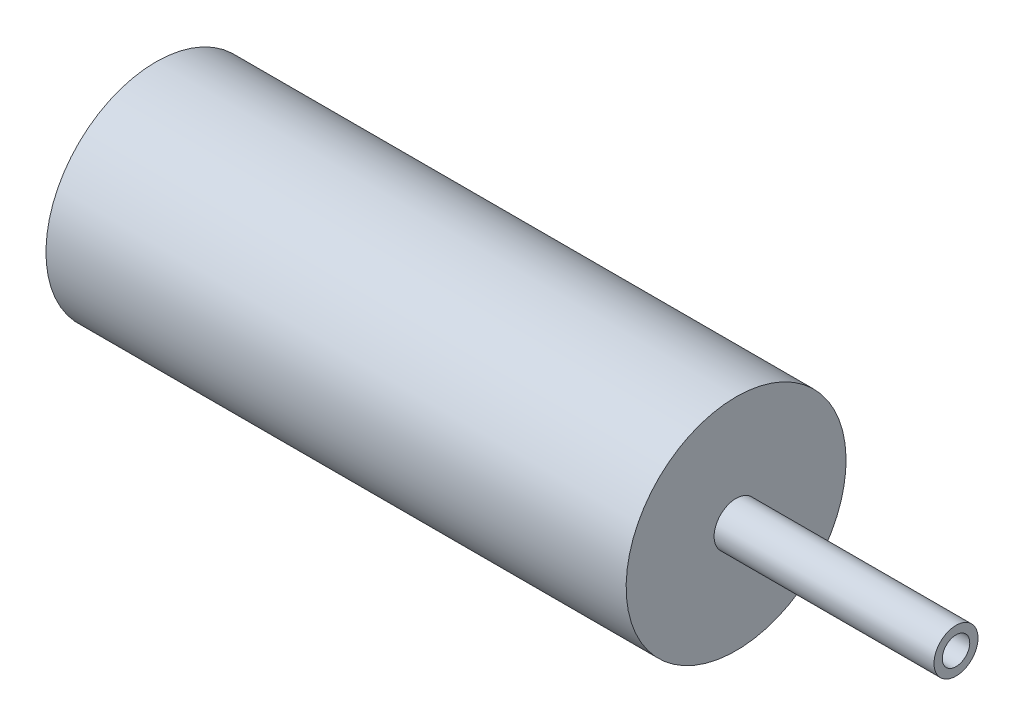
SolidWorks part; units mm, degrees
ref_plane "Ön Düzlem" through (0, 0, 0) normal (0, 0, 1) x (1, 0, 0)
ref_plane "Üst Düzlem" through (0, 0, 0) normal (0, 1, 0) x (1, 0, 0)
ref_plane "Sağ Düzlem" through (0, 0, 0) normal (1, 0, 0) x (0, 0, -1)
sketch "Sketch1" plane through (0, 0, 0) normal (0, 0, 1) x (1, 0, 0)
  line L0 (0, 0) -> (0, 1)
  line L1 (0, 1) -> (-1, 2)
  line L2 (-1, 2) -> (-7, 2)
  line L3 (-7, 2) -> (-7, 4)
  line L4 (-7, 4) -> (-10, 4)
  line L5 (-10, 4) -> (-10, 3)
  line L10 (-24.88, 5) -> (1.5, 5)
  line L11 (1.5, 5) -> (1.5, 0)
  line L12 (1.5, 0) -> (0, 0)
  line L13 (-24.88, 5) -> (-24.88, 4.5)
  line L14 (-24.88, 4.5) -> (-14.5, 4.5)
  line L15 (-14.5, 4.5) -> (-13, 3)
  line L16 (-13, 3) -> (-10, 3)
  dimension "D1" = 1
  dimension "D2" = 135
  dimension "D3" = 1
  dimension "D4" = 2
  dimension "D5" = 3
  dimension "D6" = 6
  dimension "D7" = 3
  dimension "D10" = 1.5
  dimension "D12" = 0.5
  dimension "D14" = 1.5
  dimension "D15" = 135
revolve "Revolve1" add sketch "Sketch1" angle 360 about L12
sketch "Sketch2" plane through (-7, 0, 0) normal (-1, 0, 0) x (0, 0, 1)
  line L0 (-2, 0) -> (-3.9, 0) construction
  line L1 (-2, -0.1) -> (-3.9, -0.1)
  line L2 (-2, 0.1) -> (-3.9, 0.1)
  circle A1 centre (0, 0) radius 2 construction
  arc A2 (-2, -0.1) -> (-2, 0.1) centre (-2, 0) ccw
  arc A3 (-3.9, 0.1) -> (-3.9, -0.1) centre (-3.9, 0) ccw
  point P8 (-2.95, 0)
  dimension "D1" = 0.1
  dimension "D2" = 1.9
extrude "Cut-Extrude1" cut sketch "Sketch2" against normal blind 0.5 and the other way blind 1.5
pattern_circular "CirPattern1" count 8 over 360 about axis through (0, 0, 0) along (1, 0, 0) of "Cut-Extrude1"
sketch "Sketch3" plane through (0, 0, 0) normal (-1, 0, 0) x (0, 0, 1)
  circle A0 centre (0, 0) radius 0.75
  circle A1 centre (0, 0) radius 0.625
  dimension "D1" = 1.5
  dimension "D2" = 1.25
extrude "Boss-Extrude1" add sketch "Sketch3" along normal blind 2.5
sketch "Sketch4" plane through (0, 0, 0) normal (-1, 0, 0) x (0, 0, 1)
  circle A0 centre (0, 0) radius 0.625
  dimension "D1" = 1.25
extrude "Cut-Extrude2" cut sketch "Sketch4" against normal blind 2.5
sketch "Sketch5" plane through (1.5, 0, 0) normal (1, 0, 0) x (0, 0, -1)
  circle A0 centre (0, 0) radius 0.625
  circle A1 centre (0, 0) radius 1
  dimension "D1" = 1.25
  dimension "D2" = 2
extrude "Boss-Extrude2" add sketch "Sketch5" along normal blind 10
